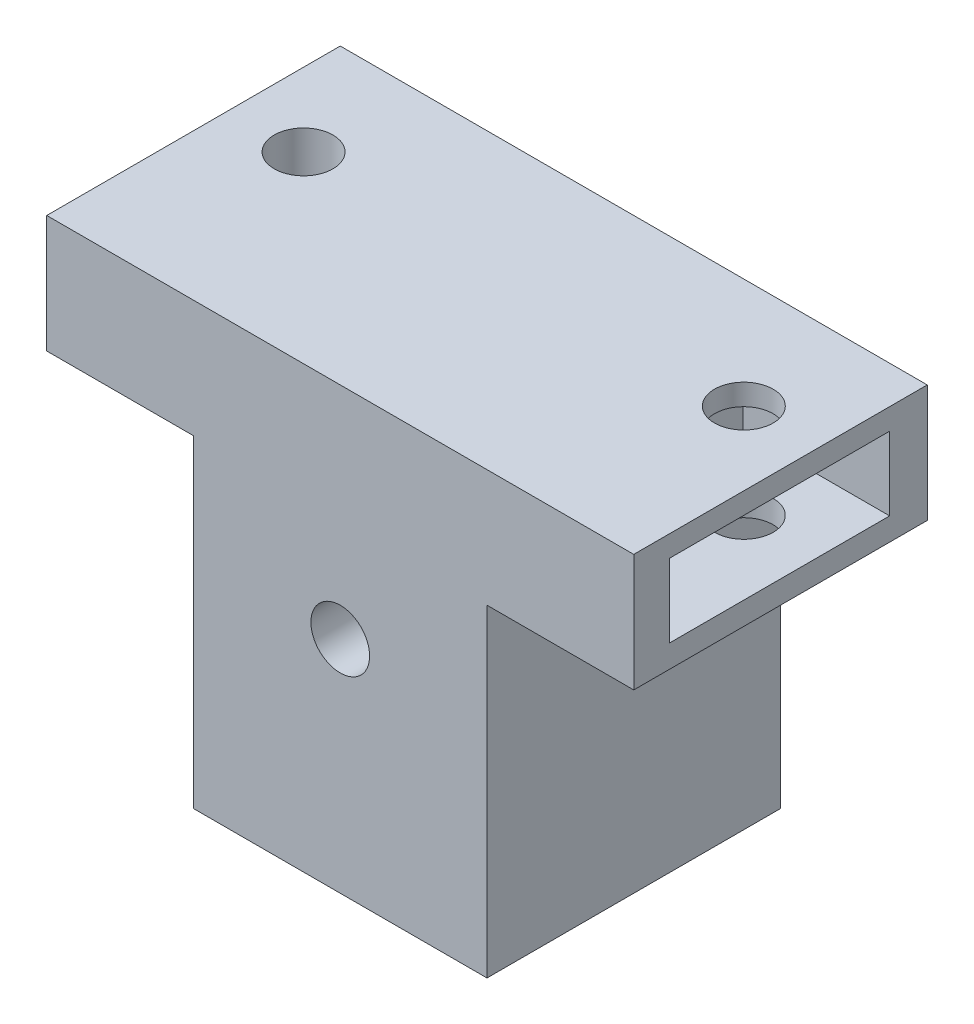
SolidWorks part; units mm, degrees
ref_plane "Front Plane" through (0, 0, 0) normal (0, 0, 1) x (1, 0, 0)
ref_plane "Top Plane" through (0, 0, 0) normal (0, 1, 0) x (1, 0, 0)
ref_plane "Right Plane" through (0, 0, 0) normal (1, 0, 0) x (0, 0, -1)
sketch "Sketch1" plane through (0, 0, 0) normal (0, 0, 1) x (1, 0, 0)
  line L1 (-10, -15) -> (10, -15)
  line L2 (-10, -15) -> (-10, 15)
  line L3 (-10, 15) -> (10, 15)
  line L4 (10, -15) -> (10, 15)
  line L5 (-10, -15) -> (10, 15) construction
  line L6 (-10, 15) -> (10, -15) construction
  point P0 (0, 0)
  dimension "D1" = 30
  dimension "D2" = 20
extrude "Boss-Extrude1" add sketch "Sketch1" along normal blind 20
sketch "Sketch2" plane through (-10, 0, 0) normal (-1, 0, 0) x (0, 0, 1)
  line L0 (20, 15) -> (20, -15) construction
  line L1 (0, 15) -> (20, 15)
  line L2 (0, 15) -> (0, 7)
  line L3 (0, 7) -> (20, 7)
  line L4 (20, 15) -> (20, 7)
  dimension "D1" = 8
extrude "Boss-Extrude2" add sketch "Sketch2" along normal blind 10
sketch "Sketch3" plane through (10, 0, 0) normal (1, 0, 0) x (0, 0, -1)
  line L0 (0, -15) -> (0, 15) construction
  line L1 (-20, 15) -> (0, 15)
  line L2 (-20, 15) -> (-20, 7)
  line L3 (-20, 7) -> (0, 7)
  line L4 (0, 15) -> (0, 7)
  dimension "D1" = 8
extrude "Boss-Extrude3" add sketch "Sketch3" along normal blind 10
sketch "Sketch4" plane through (0, 15, 0) normal (0, 1, 0) x (1, 0, 0)
  line L0 (20, 0) -> (-20, 0) construction
  line L2 (-20, -20) -> (-20, 0) construction
  line L3 (20, 0) -> (20, -20) construction
  circle A0 centre (-15, -7.5) radius 2
  circle A1 centre (15, -7.5) radius 2
  dimension "D3" = 4
  dimension "D4" = 4
  dimension "D1" = 7.5
  dimension "D2" = 7.5
  dimension "D5" = 5
  dimension "D6" = 5
extrude "Cut-Extrude1" cut sketch "Sketch4" against normal blind 10
sketch "Sketch5" plane through (0, 0, 0) normal (0, 0, -1) x (-1, 0, 0)
  circle A0 centre (0, 1.2968) radius 6
  dimension "D1" = 12
extrude "Cut-Extrude3" cut sketch "Sketch5" against normal blind 10
sketch "Sketch6" plane through (0, 0, 10) normal (0, 0, -1) x (-1, 0, 0)
  circle A0 centre (0, 0) radius 2
  dimension "D1" = 4
extrude "Cut-Extrude4" cut sketch "Sketch6" against normal blind 10
sketch "Sketch7" plane through (20, 0, 0) normal (1, 0, 0) x (0, 0, -1)
  line L1 (-2.5635, 13.5516) -> (-17.5635, 13.5516)
  line L2 (-2.5635, 13.5516) -> (-2.5635, 8.5516)
  line L3 (-2.5635, 8.5516) -> (-17.5635, 8.5516)
  line L4 (-17.5635, 13.5516) -> (-17.5635, 8.5516)
  line L5 (-2.5635, 13.5516) -> (-17.5635, 8.5516) construction
  line L6 (-2.5635, 8.5516) -> (-17.5635, 13.5516) construction
  point P0 (0.1525, 11.9658)
  dimension "D1" = 5
  dimension "D2" = 15
extrude "Cut-Extrude5" cut sketch "Sketch7" against normal blind 10
